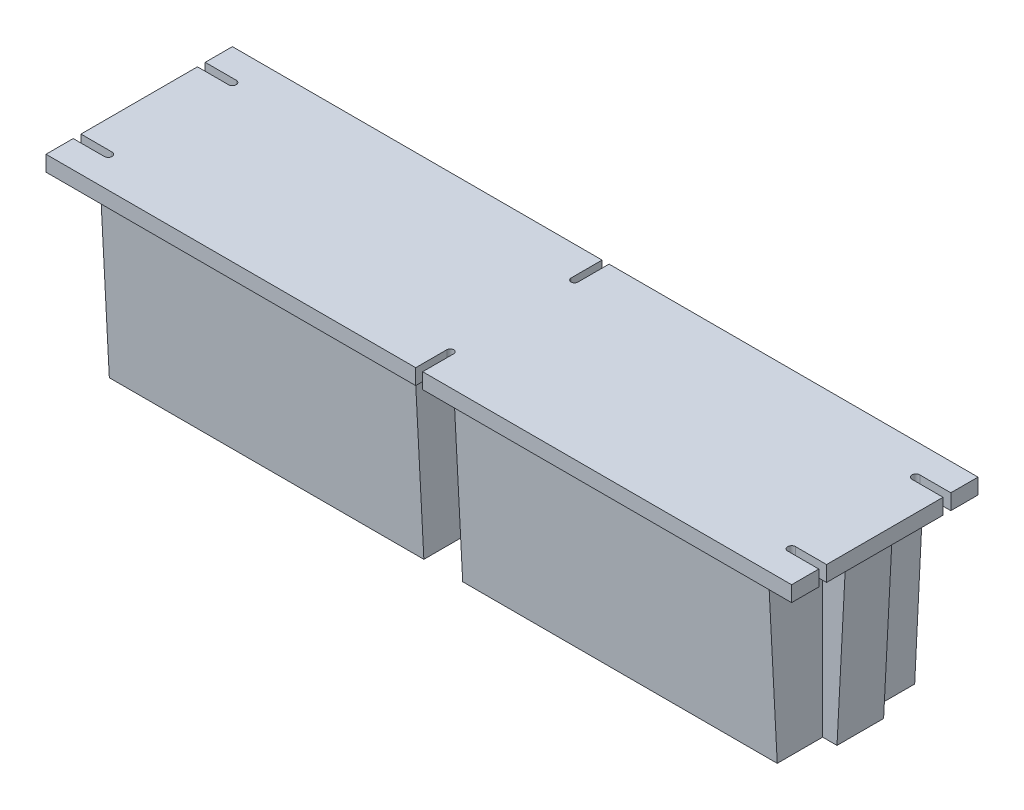
SolidWorks part; units mm, degrees
ref_plane "Front Plane" through (0, 0, 0) normal (0, 0, 1) x (1, 0, 0)
ref_plane "Top Plane" through (0, 0, 0) normal (0, 1, 0) x (1, 0, 0)
ref_plane "Right Plane" through (0, 0, 0) normal (1, 0, 0) x (0, 0, -1)
sketch "Sketch1" plane through (0, 0, 0) normal (0, 1, 0) x (1, 0, 0)
  line L1 (0, 0) -> (1219.2, 0)
  line L2 (0, 0) -> (0, 304.8)
  line L3 (0, 304.8) -> (1219.2, 304.8)
  line L4 (1219.2, 0) -> (1219.2, 304.8)
  dimension "D1" = 1219.2
  dimension "D2" = 304.8
extrude "Boss-Extrude1" add sketch "Sketch1" against normal blind 304.8 contours L2 L3 L4 L1
sketch "Sketch2" plane through (0, 0, 0) normal (0, 1, 0) x (1, 0, 0)
  line L0 (0, 260.35) -> (50.8, 260.35)
  line L1 (0, 0) -> (0, 304.8) construction
  line L2 (0, 247.65) -> (50.8, 247.65)
  line L3 (0, 304.8) -> (1219.2, 304.8) construction
  line L4 (0, 260.35) -> (0, 247.65)
  line L5 (0, 57.15) -> (50.8, 57.15)
  line L6 (0, 44.45) -> (50.8, 44.45)
  line L7 (0, 57.15) -> (0, 44.45)
  line L8 (0, 0) -> (1219.2, 0) construction
  line L9 (609.6, 304.8) -> (609.6, 0) construction
  line L10 (1219.2, 57.15) -> (1219.2, 44.45)
  line L11 (1219.2, 44.45) -> (1168.4, 44.45)
  line L12 (1219.2, 57.15) -> (1168.4, 57.15)
  line L13 (1219.2, 260.35) -> (1219.2, 247.65)
  line L14 (1219.2, 247.65) -> (1168.4, 247.65)
  line L15 (1219.2, 260.35) -> (1168.4, 260.35)
  line L16 (604.52, 304.8) -> (604.52, 254)
  line L17 (615.95, 304.8) -> (615.95, 254)
  line L18 (0, 152.4) -> (1219.2, 152.4) construction
  line L19 (1219.2, 0) -> (1219.2, 304.8) construction
  line L20 (615.95, 0) -> (615.95, 50.8)
  line L21 (604.52, 0) -> (604.52, 50.8)
  line L22 (604.52, 304.8) -> (615.95, 304.8)
  line L23 (604.52, 0) -> (615.95, 0)
  arc A0 (50.8, 247.65) -> (50.8, 260.35) centre (50.8, 254) ccw
  arc A1 (50.8, 44.45) -> (50.8, 57.15) centre (50.8, 50.8) ccw
  arc A2 (1168.4, 44.45) -> (1168.4, 57.15) centre (1168.4, 50.8) cw
  arc A3 (1168.4, 247.65) -> (1168.4, 260.35) centre (1168.4, 254) cw
  arc A4 (604.52, 254) -> (615.95, 254) centre (610.235, 254) ccw
  arc A5 (604.52, 50.8) -> (615.95, 50.8) centre (610.235, 50.8) cw
  dimension "D1" = 44.45
  dimension "D2" = 57.15
  dimension "D3" = 50.8
  dimension "D4" = 57.15
  dimension "D5" = 44.45
  dimension "D6" = 50.8
  dimension "D7" = 6.35
  dimension "D8" = 5.08
  dimension "D9" = 50.8
extrude "Cut-Extrude1" cut sketch "Sketch2" against normal through all
sketch "Sketch4" plane through (0, 0, 0) normal (-1, 0, 0) x (0, 0, 1)
  line L0 (-304.8, -25.4) -> (-279.4, -25.4)
  line L1 (-304.8, -304.8) -> (-304.8, 0) construction
  line L2 (-279.4, -25.4) -> (-264.7573, -304.8)
  line L3 (-57.15, -304.8) -> (-247.65, -304.8) construction
  line L4 (-304.8, -25.4) -> (-304.8, -304.8)
  line L5 (-40.0427, -304.8) -> (-25.4, -25.4)
  line L6 (-25.4, -25.4) -> (0, -25.4)
  line L7 (0, -304.8) -> (0, 0) construction
  line L8 (0, -25.4) -> (0, -304.8)
  line L9 (0, -304.8) -> (-40.0427, -304.8)
  line L10 (-304.8, -304.8) -> (-264.7573, -304.8)
  line L11 (-260.35, 0) -> (-304.8, 0) construction
  line L12 (0, 0) -> (-44.45, 0) construction
  dimension "D1" = 25.4
  dimension "D2" = 25.4
  dimension "D3" = 87
  dimension "D4" = 25.4
  dimension "D5" = 25.4
  dimension "D6" = 87
extrude "Cut-Extrude2" cut sketch "Sketch4" against normal through all
sketch "Sketch5" plane through (0, 1.2579, -24.0029) normal (0, -0.0523, 0.9986) x (1, 0, 0)
  line L0 (0, -306.478) -> (0, -26.6945)
  line L1 (0, -26.6945) -> (25.3753, -26.6945)
  line L2 (604.52, -26.6945) -> (0, -26.6945) construction
  line L3 (25.3753, -26.6945) -> (40.0381, -306.478)
  line L4 (604.52, -306.478) -> (0, -306.478) construction
  line L5 (40.0381, -306.478) -> (0, -306.478)
  line L6 (1219.2, -26.6945) -> (1193.8, -26.6945)
  line L7 (1219.2, -26.6945) -> (615.95, -26.6945) construction
  line L8 (1193.8, -26.6945) -> (1179.1372, -306.478)
  line L9 (1219.2, -306.478) -> (615.95, -306.478) construction
  line L10 (1179.1372, -306.478) -> (1219.2, -306.478)
  line L11 (1219.2, -26.6945) -> (1219.2, -306.478) construction
  line L12 (1219.2, -306.478) -> (1219.2, -26.6945)
  dimension "D1" = 25.3753
  dimension "D2" = 87
  dimension "D3" = 25.4
  dimension "D4" = 87
sketch "Sketch6" plane through (0, 0, 0) normal (0, 0, 1) x (1, 0, 0)
  line L0 (0, -25.4) -> (25.3753, -25.4)
  line L1 (25.3753, -25.4) -> (40.0381, -304.8)
  line L2 (40.0381, -304.8) -> (0, -304.8)
  line L3 (0, -304.8) -> (0, -25.4)
  line L4 (1193.8, -25.4) -> (1219.2, -25.4)
  line L5 (1219.2, -25.4) -> (1219.2, -304.8)
  line L6 (1219.2, -304.8) -> (1179.1372, -304.8)
  line L7 (1179.1372, -304.8) -> (1193.8, -25.4)
extrude "Cut-Extrude4" cut sketch "Sketch6" against normal through all
sketch "Sketch7" plane through (0, 0, 0) normal (0, 0, 1) x (1, 0, 0)
  line L0 (1155.7, -304.8) -> (1155.7, -25.4)
  line L1 (1179.1372, -304.8) -> (615.95, -304.8) construction
  line L2 (1193.8, -25.4) -> (615.95, -25.4) construction
  line L3 (1155.7, -25.4) -> (1219.2, -25.4)
  line L4 (1219.2, -25.4) -> (1219.2, -304.8)
  line L5 (1219.2, -304.8) -> (1155.7, -304.8)
  line L6 (0, -25.4) -> (63.5, -25.4)
  line L7 (604.52, -25.4) -> (25.3753, -25.4) construction
  line L8 (63.5, -25.4) -> (63.5, -304.8)
  line L9 (604.52, -304.8) -> (40.0381, -304.8) construction
  line L10 (0, -25.4) -> (0, -304.8)
  line L11 (0, -304.8) -> (63.5, -304.8)
  line L12 (577.85, -25.4) -> (641.35, -25.4)
  line L13 (604.52, -25.4) -> (0, -25.4) construction
  line L14 (641.35, -25.4) -> (641.35, -304.8)
  line L15 (641.35, -304.8) -> (577.85, -304.8)
  line L16 (577.85, -304.8) -> (577.85, -25.4)
  line L17 (1219.2, -25.4) -> (1219.2, 0) construction
  dimension "D1" = 63.5
  dimension "D2" = 63.5
  dimension "D3" = 63.5
  dimension "D4" = 577.85
extrude "Cut-Extrude5" cut sketch "Sketch7" against normal blind 114.3
sketch "Sketch8" plane through (0, 0, 0) normal (0, 1, 0) x (1, 0, 0)
  line L0 (0, 152.4) -> (1219.2, 152.4) construction
  line L1 (0, 57.15) -> (0, 247.65) construction
  line L2 (1219.2, 57.15) -> (1219.2, 247.65) construction
ref_plane "Plane1" through (0, 0, -152.4) normal (0, 0, -1) x (-1, 0, 0)
mirror "Mirror1" about plane through (0, 0, -152.4) normal (0, 0, -1) of "Cut-Extrude5"
